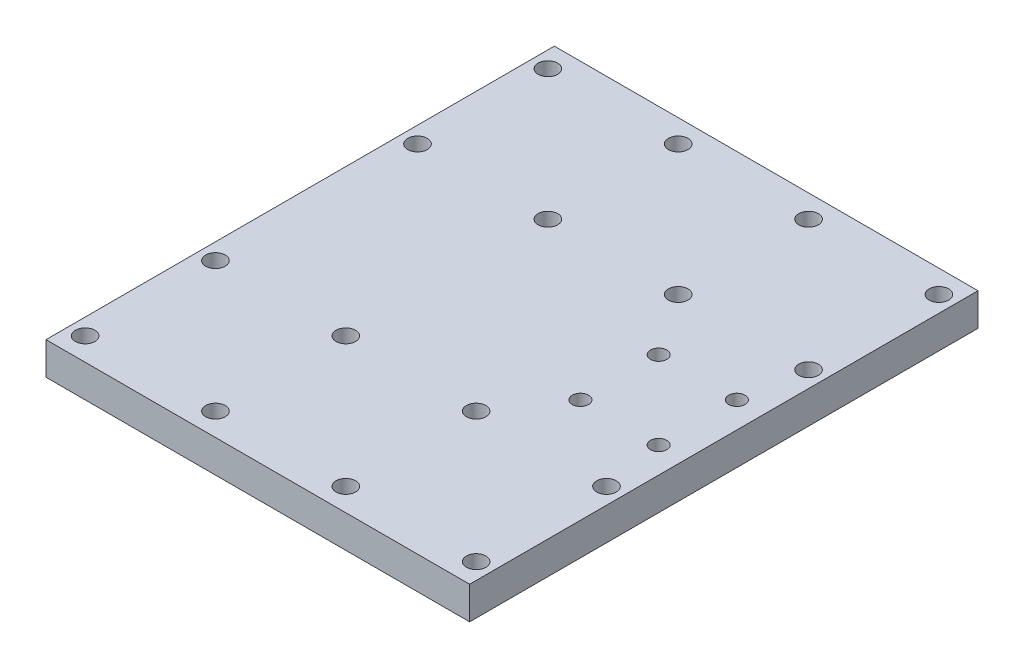
SolidWorks part; units mm, degrees
ref_plane "Front Plane" through (0, 0, 0) normal (0, 0, 1) x (1, 0, 0)
ref_plane "Top Plane" through (0, 0, 0) normal (0, 1, 0) x (1, 0, 0)
ref_plane "Right Plane" through (0, 0, 0) normal (1, 0, 0) x (0, 0, -1)
sketch "Sketch1" plane through (0, 0, 0) normal (0, 1, 0) x (1, 0, 0)
  line L0 (0, 34.4931) -> (5, 34.4931)
  line L1 (0, 34.4931) -> (0, -121.5069)
  line L2 (0, -121.5069) -> (130, -121.5069)
  line L3 (0, 34.4931) -> (130, 34.4931)
  line L4 (130, -121.5069) -> (130, 34.4931)
  line L5 (5, 34.4931) -> (5, 27.4931)
  line L11 (45, -74.5069) -> (45, -114.5069)
  line L19 (125, -74.5069) -> (125, -114.5069)
  circle A0 centre (5, 27.4931) radius 3
  circle A1 centre (45, 27.4931) radius 3
  circle A2 centre (45, -12.5069) radius 3
  circle A3 centre (5, -12.5069) radius 3
  circle A4 centre (85, 27.4931) radius 3
  circle A5 centre (125, 27.4931) radius 3
  circle A6 centre (85, -12.5069) radius 3
  circle A7 centre (125, -12.5069) radius 3
  circle A8 centre (85, -74.5069) radius 3
  circle A9 centre (125, -74.5069) radius 3
  circle A10 centre (125, -114.5069) radius 3
  circle A11 centre (85, -114.5069) radius 3
  circle A12 centre (5, -74.5069) radius 3
  circle A13 centre (45, -74.5069) radius 3
  circle A14 centre (5, -114.5069) radius 3
  circle A15 centre (45, -114.5069) radius 3
extrude "Boss-Extrude1" add sketch "Sketch1" along normal blind 10
sketch "Sketch2" plane through (0, 10, 0) normal (0, 1, 0) x (1, 0, 0)
  circle A0 centre (98, -31.5069) radius 2.5
  circle A1 centre (98, -55.5069) radius 2.5
  circle A2 centre (122, -55.5069) radius 2.5
  circle A3 centre (122, -31.5069) radius 2.5
extrude "Cut-Extrude1" cut sketch "Sketch2" against normal blind 10
sketch "Sketch3" plane through (0, 0, -34.4931) normal (0, 0, -1) x (-1, 0, 0)
  line L1 (0, 10) -> (-130, 10)
  line L2 (0, 10) -> (0, 0)
  line L3 (0, 0) -> (-130, 0)
  line L4 (-130, 10) -> (-130, 0)
extrude "Boss-Extrude2" add sketch "Sketch3" along normal blind 10
sketch "Sketch4" plane through (0, 0, 121.5069) normal (0, 0, 1) x (1, 0, 0)
  line L1 (0, 0) -> (130, 0)
  line L2 (0, 0) -> (0, 10)
  line L3 (0, 10) -> (130, 10)
  line L4 (130, 0) -> (130, 10)
extrude "Boss-Extrude3" add sketch "Sketch4" along normal blind 10
sketch "Sketch5" plane through (0, 0, 131.5069) normal (0, 0, 1) x (1, 0, 0)
  line L1 (0, 0) -> (130, 0)
  line L2 (0, 0) -> (0, 10)
  line L3 (0, 10) -> (130, 10)
  line L4 (130, 0) -> (130, 10)
extrude "Cut-Extrude2" cut sketch "Sketch5" against normal blind 12.25
sketch "Sketch6" plane through (0, 10, 0) normal (0, 1, 0) x (1, 0, 0)
  line L0 (130, -119.2569) -> (130, 44.4931) construction
  line L1 (0, 44.4931) -> (130, 44.4931)
  line L2 (0, 44.4931) -> (0, 32.2431)
  line L3 (0, 32.2431) -> (130, 32.2431)
  line L4 (130, 44.4931) -> (130, 32.2431)
  dimension "D1" = 12.25
extrude "Cut-Extrude3" cut sketch "Sketch6" against normal blind 20
sketch "Sketch7" plane through (0, 0, -32.2431) normal (0, 0, -1) x (-1, 0, 0)
  line L1 (0, 10) -> (-130, 10)
  line L2 (0, 10) -> (0, 0)
  line L3 (0, 0) -> (-130, 0)
  line L4 (-130, 10) -> (-130, 0)
extrude "Boss-Extrude5" add sketch "Sketch7" along normal blind 2.25
sketch "Sketch8" plane through (0, 0, 119.2569) normal (0, 0, 1) x (1, 0, 0)
  line L1 (0, 10) -> (130, 10)
  line L2 (0, 10) -> (0, 0)
  line L3 (0, 0) -> (130, 0)
  line L4 (130, 10) -> (130, 0)
extrude "Boss-Extrude6" add sketch "Sketch8" along normal blind 2.25
sketch "Sketch10" plane through (0, 0, 121.5069) normal (0, 0, 1) x (1, 0, 0)
  line L1 (0, 0) -> (130, 0)
  line L2 (0, 0) -> (0, 10)
  line L3 (0, 10) -> (130, 10)
  line L4 (130, 0) -> (130, 10)
extrude "Boss-Extrude8" add sketch "Sketch10" along normal blind 10
sketch "Sketch11" plane through (0, 0, -34.4931) normal (0, 0, -1) x (-1, 0, 0)
  line L1 (0, 10) -> (-130, 10)
  line L2 (0, 10) -> (0, 0)
  line L3 (0, 0) -> (-130, 0)
  line L4 (-130, 10) -> (-130, 0)
extrude "Boss-Extrude10" add sketch "Sketch11" along normal blind 7
sketch "Sketch12" plane through (0, 0, -41.4931) normal (0, 0, -1) x (-1, 0, 0)
  line L0 (0, 10) -> (-130, 10) construction
  line L1 (-130, 10) -> (0, 10)
  line L2 (-130, 10) -> (-130, 0)
  line L3 (-130, 0) -> (0, 0)
  line L4 (0, 10) -> (0, 0)
extrude "Cut-Extrude4" cut sketch "Sketch12" against normal blind 7
sketch "Sketch14" plane through (0, 0, 131.5069) normal (0, 0, 1) x (1, 0, 0)
  line L1 (0, 0) -> (130, 0)
  line L2 (0, 0) -> (0, 10)
  line L3 (0, 10) -> (130, 10)
  line L4 (130, 0) -> (130, 10)
extrude "Cut-Extrude5" cut sketch "Sketch14" against normal blind 10
